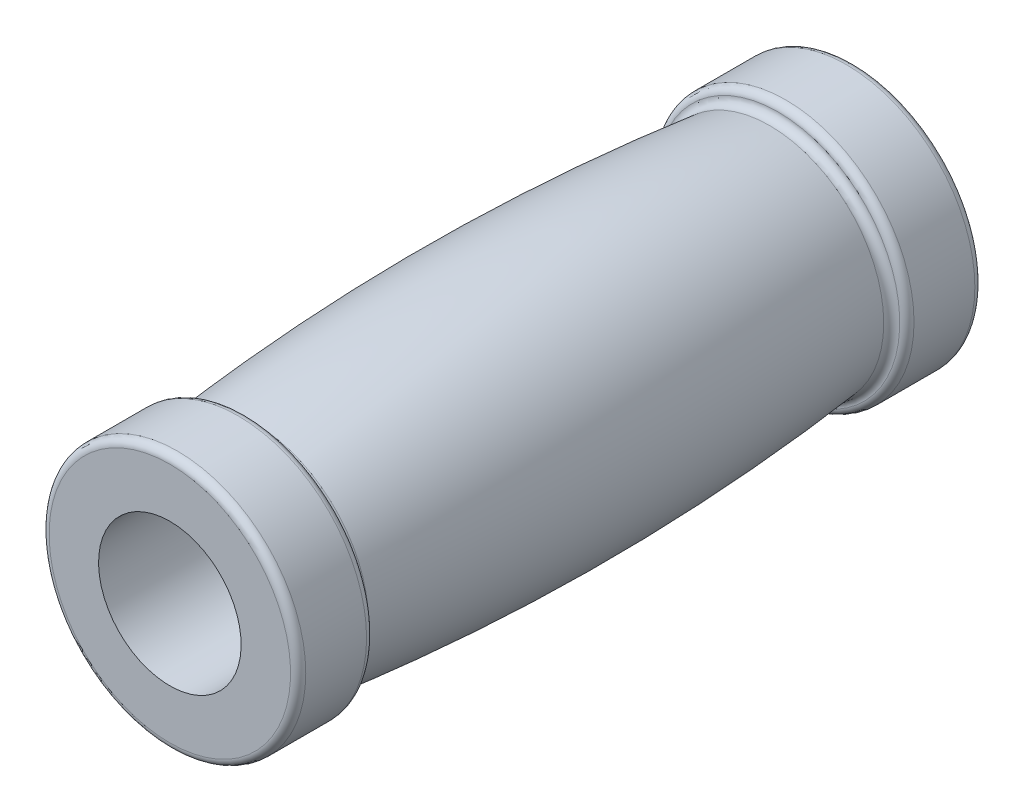
SolidWorks part; units mm, degrees
ref_plane "Front Plane" through (0, 0, 0) normal (0, 0, 1) x (1, 0, 0)
ref_plane "Top Plane" through (0, 0, 0) normal (0, 1, 0) x (1, 0, 0)
ref_plane "Right Plane" through (0, 0, 0) normal (1, 0, 0) x (0, 0, -1)
sketch "Sketch1" plane through (0, 0, 0) normal (1, 0, 0) x (0, 0, -1)
  line L0 (-57.15, 0) -> (57.15, 0) construction
  line L1 (57.15, 11.9062) -> (57.15, -11.9062) construction
  line L2 (57.15, 11.9062) -> (57.15, 21.4312) construction
  dimension "Length" = 114.3
  dimension "For OD" = 23.8125
  dimension "Material Thickness" = 9.525
sketch "Sketch2" plane through (0, 0, 0) normal (1, 0, 0) x (0, 0, -1)
  line L0 (57.15, 0) -> (-57.15, 0) construction
  line L1 (57.15, 11.9062) -> (57.15, -11.9063) construction
  line L2 (57.15, 11.9062) -> (57.15, 21.4312) construction
  line L3 (57.15, 11.9062) -> (57.15, 21.4312) construction
  line L4 (57.15, 21.4312) -> (-57.15, 21.4312) construction
  line L5 (-57.15, 20.1613) -> (-57.15, 11.9062)
  line L6 (-57.15, 11.9062) -> (57.15, 11.9062)
  line L7 (-55.88, 21.4313) -> (-45.72, 21.4312)
  line L8 (-44.45, 20.1612) -> (-44.45, 20.3122)
  line L9 (0, 11.9062) -> (0, 21.4312) construction
  line L10 (-45.72, 21.4312) -> (-45.72, 19.05) construction
  line L11 (-45.72, 19.05) -> (-45.72, 16.6687) construction
  line L12 (-45.72, 16.6687) -> (-45.72, 14.2875) construction
  line L13 (44.45, 20.1612) -> (44.45, 20.3122)
  line L14 (55.88, 21.4313) -> (45.72, 21.4312)
  line L15 (57.15, 20.1613) -> (57.15, 11.9062)
  line L16 (-45.72, 14.2875) -> (-45.72, 11.9062) construction
  arc A0 (43.0399, 19.05) -> (-43.0399, 19.05) centre (0, -368.7217) ccw
  arc A1 (-44.45, 20.3122) -> (-43.0399, 19.05) centre (-43.18, 20.3122) ccw
  arc A2 (-45.72, 21.4312) -> (-44.45, 20.1612) centre (-45.72, 20.1612) cw
  arc A3 (-55.88, 21.4313) -> (-57.15, 20.1613) centre (-55.88, 20.1613) ccw
  arc A4 (44.45, 20.3122) -> (43.0399, 19.05) centre (43.18, 20.3122) cw
  arc A5 (45.72, 21.4312) -> (44.45, 20.1612) centre (45.72, 20.1612) ccw
  arc A6 (55.88, 21.4313) -> (57.15, 20.1613) centre (55.88, 20.1613) cw
  point P21 (-44.45, 21.4312)
  dimension "D2" = 1.27
  dimension "D1" = 12.7
  dimension "D3" = 114.3
  dimension "D4" = 9.525
  dimension "D5" = 23.8125
revolve "Revolve1" add sketch "Sketch2" angle 360 about L0
sketch "Sketch3" plane through (0, 0, 57.15) normal (0, 0, 1) x (1, 0, 0)
  line L0 (11.9063, 0) -> (21.4312, 0) construction
  line L1 (0, 11.9063) -> (0, 21.4312) construction
  circle A1 centre (0, 0) radius 11.9063 construction
equation "\"D3@Sketch2\"=\"Length@Sketch1\""
equation "\"D4@Sketch2\"=\"Material Thickness@Sketch1\""
equation "\"D5@Sketch2\"=\"For OD@Sketch1\""
